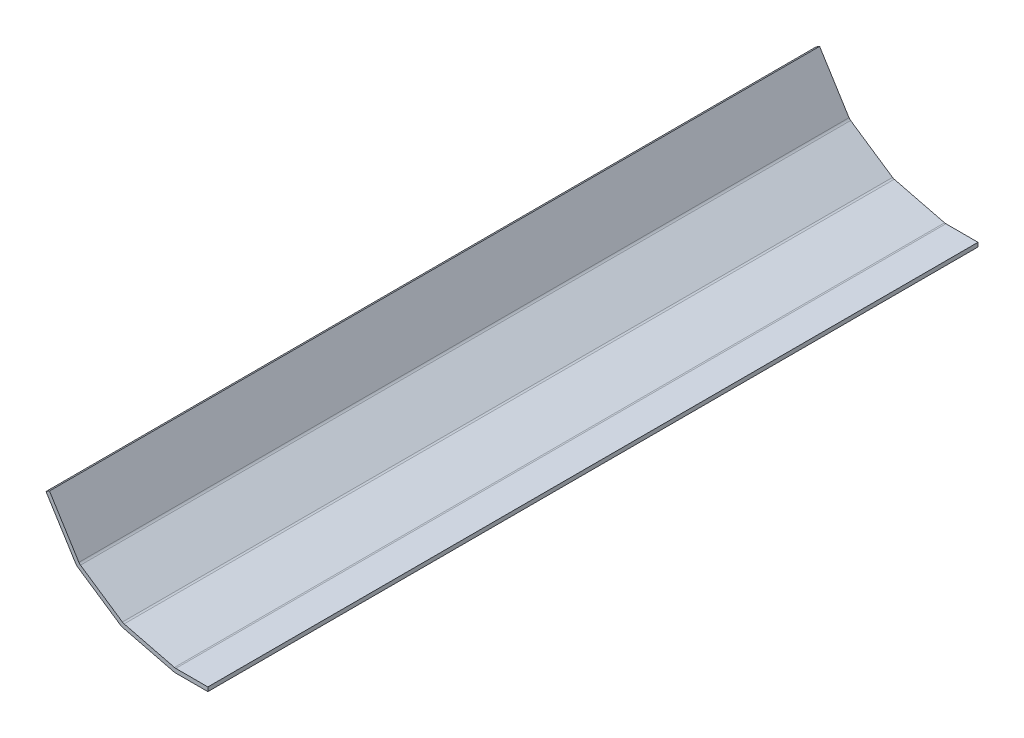
SolidWorks part; units mm, degrees
ref_plane "Front Plane" through (0, 0, 0) normal (0, 0, 1) x (1, 0, 0)
ref_plane "Top Plane" through (0, 0, 0) normal (0, 1, 0) x (1, 0, 0)
ref_plane "Right Plane" through (0, 0, 0) normal (1, 0, 0) x (0, 0, -1)
sketch "Tangent bend section, formed state profile" plane through (0, 0, 0) normal (0, 0, 1) x (1, 0, 0)
  line L0 (152, 3) -> (140.2456, 3)
  line L1 (139.7617, 3.0594) -> (121.3422, 7.6519)
  line L2 (120.7076, 7.9344) -> (105.3524, 18.2916)
  line L3 (104.7747, 18.8899) -> (94, 36.133)
  line L4 (94, 36.133) -> (92.7279, 35.3382)
  line L5 (92.7279, 35.3382) -> (103.5027, 18.095)
  line L6 (104.5136, 17.0481) -> (119.8688, 6.6909)
  line L7 (120.9793, 6.1965) -> (139.3988, 1.604)
  line L8 (140.2456, 1.5) -> (152, 1.5)
  line L9 (152, 1.5) -> (152, 3)
  arc A0 (140.2456, 3) -> (139.7617, 3.0594) centre (140.2456, 5) cw
  arc A1 (121.3422, 7.6519) -> (120.7076, 7.9344) centre (121.826, 9.5925) cw
  arc A2 (105.3524, 18.2916) -> (104.7747, 18.8899) centre (106.4708, 19.9497) cw
  arc A3 (103.5027, 18.095) -> (104.5136, 17.0481) centre (106.4708, 19.9497) ccw
  arc A4 (119.8688, 6.6909) -> (120.9793, 6.1965) centre (121.826, 9.5925) ccw
  arc A5 (139.3988, 1.604) -> (140.2456, 1.5) centre (140.2456, 5) ccw
extrude "Tangent bend section, formed state" add sketch "Tangent bend section, formed state profile" along normal blind 282
